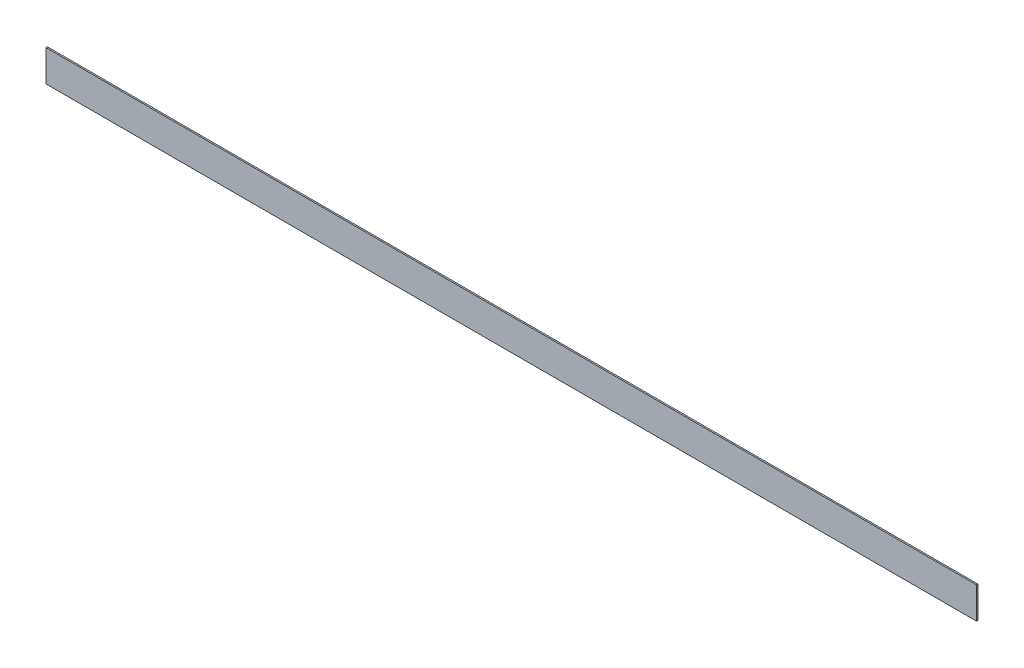
SolidWorks part; units mm, degrees
ref_plane "Front Plane" through (0, 0, 0) normal (0, 0, 1) x (1, 0, 0)
ref_plane "Top Plane" through (0, 0, 0) normal (0, 1, 0) x (1, 0, 0)
ref_plane "Right Plane" through (0, 0, 0) normal (1, 0, 0) x (0, 0, -1)
sketch "Sketch1" plane through (0, 0, 0) normal (0, 0, 1) x (1, 0, 0)
  line L1 (-665.5, -22.5) -> (665.5, -22.5)
  line L2 (-665.5, -22.5) -> (-665.5, 22.5)
  line L3 (-665.5, 22.5) -> (665.5, 22.5)
  line L4 (665.5, -22.5) -> (665.5, 22.5)
  line L5 (-665.5, -22.5) -> (665.5, 22.5) construction
  line L6 (-665.5, 22.5) -> (665.5, -22.5) construction
  point P0 (0, 0)
  dimension "D1" = 1331
  dimension "D2" = 45
extrude "Boss-Extrude1" add sketch "Sketch1" along normal blind 2
